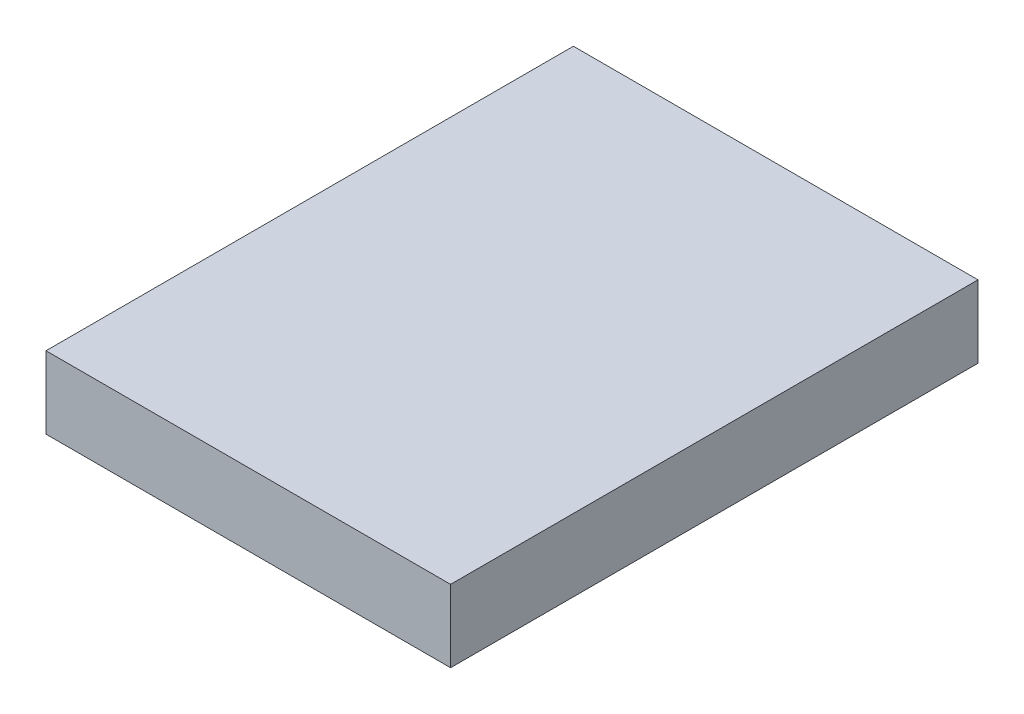
SolidWorks part; units mm, degrees
ref_plane "Front Plane" through (0, 0, 0) normal (0, 0, 1) x (1, 0, 0)
ref_plane "Top Plane" through (0, 0, 0) normal (0, 1, 0) x (1, 0, 0)
ref_plane "Right Plane" through (0, 0, 0) normal (1, 0, 0) x (0, 0, -1)
sketch "Sketch1" plane through (0, 0, 0) normal (0, 1, 0) x (1, 0, 0)
  line L1 (0, 0) -> (112, 0)
  line L2 (0, 0) -> (0, 146)
  line L3 (0, 146) -> (112, 146)
  line L4 (112, 0) -> (112, 146)
  dimension "D1" = 146
  dimension "D2" = 112
extrude "Boss-Extrude1" add sketch "Sketch1" along normal blind 20
